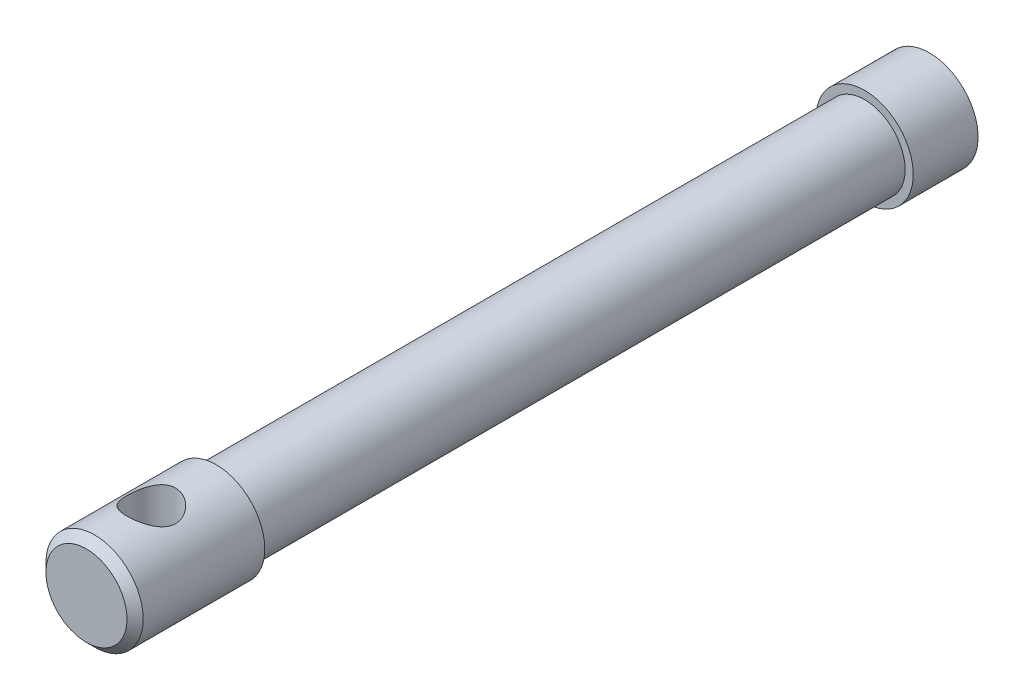
SolidWorks part; units mm, degrees
material "Alloy Steel"
ref_plane "Front Plane" through (0, 0, 0) normal (0, 0, 1) x (1, 0, 0)
ref_plane "Top Plane" through (0, 0, 0) normal (0, 1, 0) x (1, 0, 0)
ref_plane "Right Plane" through (0, 0, 0) normal (1, 0, 0) x (0, 0, -1)
sketch "Sketch1" plane through (0, 0, 0) normal (0, 0, 1) x (1, 0, 0)
  circle A0 centre (0, 0) radius 7.9375
  dimension "D1" = 15.875
extrude "Boss-Extrude1" add sketch "Sketch1" against normal blind 165.1
sketch "Sketch2" plane through (0, 0, 0) normal (0, 0, 1) x (1, 0, 0)
  circle A0 centre (0, 0) radius 9.525
  dimension "D1" = 19.05
extrude "Boss-Extrude2" add sketch "Sketch2" against normal blind 25.4
chamfer "Chamfer2" distance 1.5875 angle 45 1 edges at (9.525, 0, 0)
sketch "Sketch3" plane through (0, 0, 0) normal (0, 1, 0) x (1, 0, 0)
  circle A0 centre (0, 12.7) radius 4.7625
  dimension "D2" = 9.525
  dimension "D1" = 12.7
extrude "Cut-Extrude2" cut sketch "Sketch3" against normal blind 41.148 and the other way blind 39.878
sketch "Sketch4" plane through (0, 0, -165.1) normal (0, 0, -1) x (-1, 0, 0)
  circle A0 centre (0, 0) radius 9.525
  dimension "D1" = 19.05
extrude "Boss-Extrude3" add sketch "Sketch4" against normal blind 12.7
